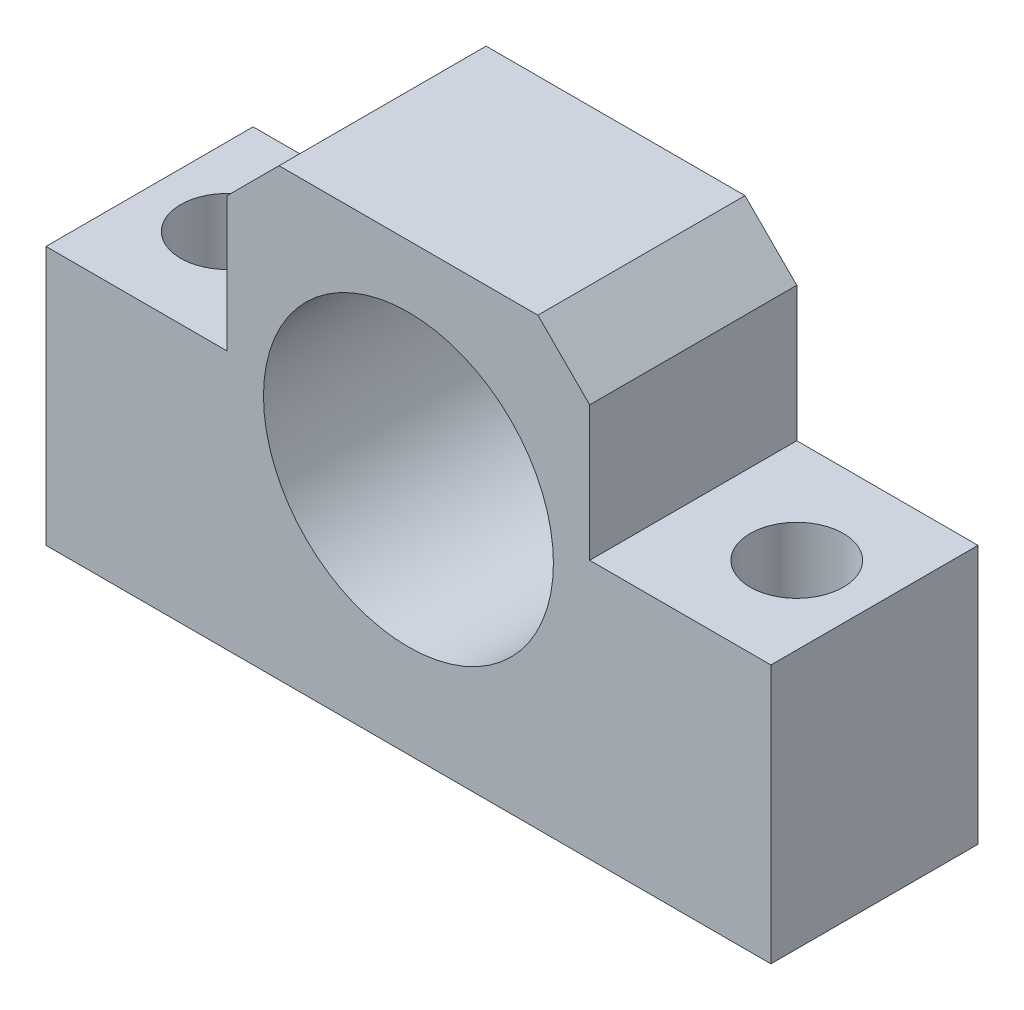
SolidWorks part; units mm, degrees
ref_plane "前视基准面" through (0, 0, 0) normal (0, 0, 1) x (1, 0, 0)
ref_plane "上视基准面" through (0, 0, 0) normal (0, 1, 0) x (1, 0, 0)
ref_plane "右视基准面" through (0, 0, 0) normal (1, 0, 0) x (0, 0, -1)
ref_plane "基准面4" through (0, 0, 20) normal (0, 0, 1) x (1, 0, 0)
sketch "草图1" plane through (0, 0, 20) normal (0, 0, 1) x (1, 0, 0)
  line L0 (-35, 30.5) -> (-35, -12.5)
  line L1 (-35, -12.5) -> (35, -12.5)
  line L2 (35, -12.5) -> (35, 30.5)
  line L3 (35, 30.5) -> (-35, 30.5)
extrude "凸台-拉伸1" add sketch "草图1" against normal blind 20
sketch "草图2" plane through (0, 0, 0) normal (0, 0, -1) x (-1, 0, 0)
  line L0 (17.5, 30.5) -> (17.5, 12.5)
  line L1 (17.5, 12.5) -> (35, 12.5)
  line L2 (35, 12.5) -> (35, 30.5)
  line L3 (35, 30.5) -> (17.5, 30.5)
extrude "切除-拉伸1" cut sketch "草图2" against normal through all
sketch "草图3" plane through (0, 0, 0) normal (0, 0, -1) x (-1, 0, 0)
  line L0 (-35, 12.5) -> (-17.5, 12.5)
  line L1 (-17.5, 12.5) -> (-17.5, 30.5)
  line L2 (-17.5, 30.5) -> (-35, 30.5)
  line L3 (-35, 30.5) -> (-35, 12.5)
extrude "切除-拉伸2" cut sketch "草图3" against normal through all
ref_plane "基准面5" through (0, 0, 17) normal (0, 0, 1) x (1, 0, 0)
ref_plane "基准面6" through (0, 0, 22) normal (0, 0, -1) x (0, 1, 0)
hole_wizard "Ø9.0 (9) 直径孔1" positions "草图10" profile "草图9" hole size "Ø9.0" standard "ANSI Metric"
sketch "草图10" plane through (0, 12.5, 0) normal (0, 1, 0) x (1, 0, 0)
  point P0 (27.5, -10)
sketch "草图9" plane through (27.5, 12.5, 10) normal (1, 0, 0) x (0, 0, 1)
  line L0 (0, 0) -> (0, 25)
  line L1 (0, 25) -> (4.5, 25)
  line L2 (4.5, 25) -> (4.5, 0)
  line L5 (4.5, 0) -> (0, 0)
  line L11 (0, -6.35) -> (0, 107.95) construction
  dimension "通孔孔直径" = 9
  dimension "通孔孔深度" = 25
hole_wizard "Ø9.0 (9) 直径孔2" positions "草图12" profile "草图11" hole size "Ø9.0" standard "ANSI Metric"
sketch "草图12" plane through (0, -12.5, 0) normal (0, -1, 0) x (-1, 0, 0)
  point P0 (27.5, -10)
sketch "草图11" plane through (-27.5, -12.5, 10) normal (1, 0, 0) x (0, 0, -1)
  line L0 (0, 0) -> (0, 43)
  line L1 (0, 43) -> (4.5, 43)
  line L2 (4.5, 43) -> (4.5, 0)
  line L5 (4.5, 0) -> (0, 0)
  line L11 (0, -6.35) -> (0, 107.95) construction
  dimension "通孔孔直径" = 9
  dimension "通孔孔深度" = 43
hole_wizard "M24 六角头螺栓的柱形沉头孔1" positions "草图14" profile "草图13" counterbore size "M24" standard "ANSI Metric"
sketch "草图14" plane through (0, 0, 20) normal (0, 0, 1) x (1, 0, 0)
  point P0 (0, 10.5)
sketch "草图13" plane through (0, 10.5, 20) normal (1, 0, 0) x (0, -1, 0)
  line L0 (0, 0) -> (0, 20)
  line L1 (0, 20) -> (12.5, 20)
  line L3 (12.5, 20) -> (12.5, 12)
  line L4 (12.5, 12) -> (16, 12)
  line L5 (16, 12) -> (16, 0)
  line L7 (16, 0) -> (0, 0)
  line L11 (0, -6.35) -> (0, 107.95) construction
  dimension "通孔孔直径" = 25
  dimension "通孔孔深度" = 20
  dimension "柱形沉头孔直径" = 32
  dimension "柱形沉头孔深度" = 12
chamfer "倒角1" distance 5 angle 45 2 edges at (17.5, 30.5, 10) (-17.5, 30.5, 10)
sketch "草图15" plane through (0, 0, 8) normal (0, 0, 1) x (1, 0, 0)
  circle A0 centre (0, 10.5) radius 14
  circle A1 centre (0, 10.5) radius 16
extrude "凸台-拉伸3" add sketch "草图15" along normal up to surface (12 mm away) up to face at (16, 10.5, 20)
sketch "草图16" plane through (0, 0, 0) normal (0, 0, -1) x (-1, 0, 0)
  circle A0 centre (0, 10.5) radius 14
extrude "切除-拉伸7" cut sketch "草图16" against normal blind 10
